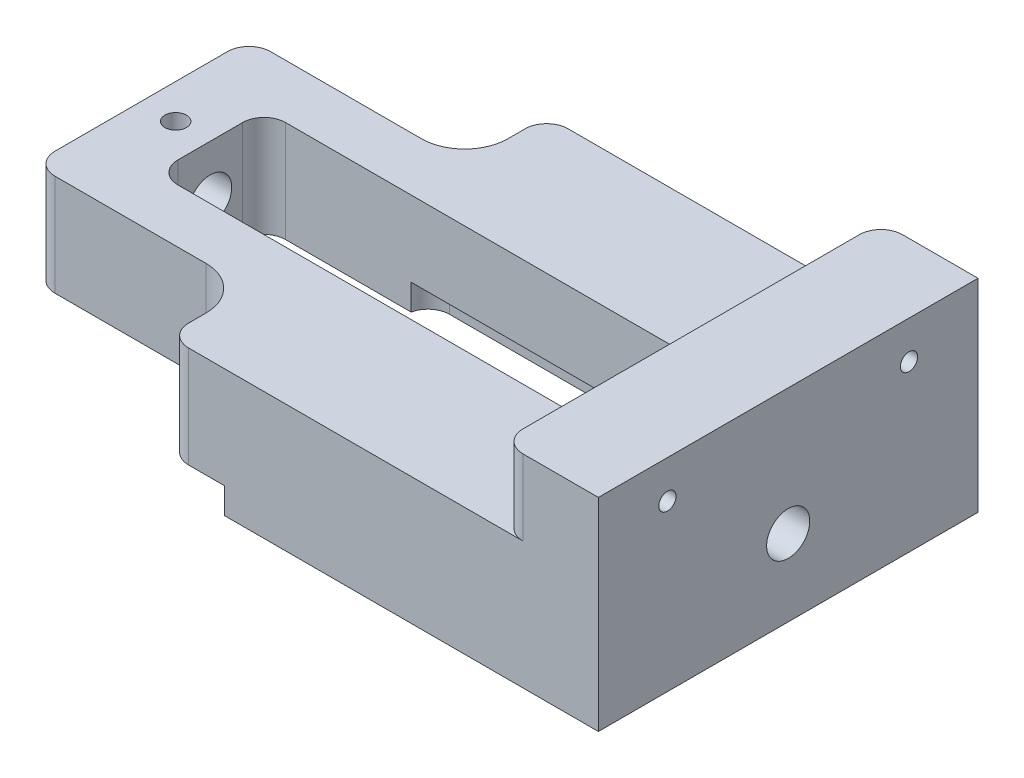
SolidWorks part; units mm, degrees
ref_plane "Front Plane" through (0, 0, 0) normal (0, 0, 1) x (1, 0, 0)
ref_plane "Top Plane" through (0, 0, 0) normal (0, 1, 0) x (1, 0, 0)
ref_plane "Right Plane" through (0, 0, 0) normal (1, 0, 0) x (0, 0, -1)
sketch "Sketch1" plane through (0, 0, 0) normal (0, 1, 0) x (1, 0, 0)
  line L0 (-256.2885, 0) -> (256.2885, 0) construction
  line L1 (-256.2885, 40) -> (-256.2885, -40)
  line L2 (-246.2885, -50) -> (-176.2885, -50)
  line L3 (-156.2885, -70) -> (-156.2885, -78)
  line L4 (-146.2885, -88) -> (43.7115, -88)
  line L5 (43.7115, -88) -> (43.7115, 88)
  line L6 (-146.2885, 88) -> (43.7115, 88)
  line L7 (-246.2885, 50) -> (-176.2885, 50)
  line L8 (-156.2885, 70) -> (-156.2885, 78)
  line L9 (-224.2885, 15) -> (-224.2885, -15)
  line L10 (-214.2885, -25) -> (-9.2885, -25)
  line L11 (0.7115, -15) -> (0.7115, 15)
  line L12 (-214.2885, 25) -> (-9.2885, 25)
  arc A0 (-156.2885, -70) -> (-176.2885, -50) centre (-176.2885, -70) ccw
  arc A1 (-246.2885, -50) -> (-256.2885, -40) centre (-246.2885, -40) cw
  arc A2 (-146.2885, -88) -> (-156.2885, -78) centre (-146.2885, -78) cw
  arc A3 (-146.2885, 88) -> (-156.2885, 78) centre (-146.2885, 78) ccw
  arc A4 (-156.2885, 70) -> (-176.2885, 50) centre (-176.2885, 70) cw
  arc A5 (-246.2885, 50) -> (-256.2885, 40) centre (-246.2885, 40) ccw
  arc A6 (0.7115, -15) -> (-9.2885, -25) centre (-9.2885, -15) cw
  arc A7 (-214.2885, -25) -> (-224.2885, -15) centre (-214.2885, -15) cw
  arc A8 (0.7115, 15) -> (-9.2885, 25) centre (-9.2885, 15) ccw
  arc A9 (-214.2885, 25) -> (-224.2885, 15) centre (-214.2885, 15) ccw
  point P0 (-56.2885, -88)
  point P4 (0, 0)
  point P12 (-156.2885, -50)
  point P15 (-256.2885, -50)
  point P18 (-156.2885, -88)
  point P29 (43.7115, 0)
  point P37 (-224.2885, -25)
  point P39 (0.7115, 0)
  point P44 (-224.2885, 0)
  dimension "D6" = 20
  dimension "D7" = 10
  dimension "D8" = 10
  dimension "D12" = 10
  dimension "D1" = 50
  dimension "D2" = 100
  dimension "D3" = 88
  dimension "D4" = 200
  dimension "D5" = 100
  dimension "D9" = 32
  dimension "D10" = 25
  dimension "D11" = 43
extrude "Boss-Extrude1" add sketch "Sketch1" along normal blind 47
sketch "Sketch2" plane through (0, 47, 0) normal (0, 1, 0) x (1, 0, 0)
  line L0 (43.7115, -88) -> (43.7115, 88) construction
  line L1 (43.7115, -88) -> (43.7115, 88)
  line L2 (43.7115, 88) -> (8.7115, 88)
  line L3 (43.7115, 88) -> (-146.2885, 88) construction
  line L4 (43.7115, -88) -> (8.7115, -88)
  line L5 (-146.2885, -88) -> (43.7115, -88) construction
  line L6 (-1.2885, -78) -> (-1.2885, 78)
  arc A0 (8.7115, -88) -> (-1.2885, -78) centre (8.7115, -78) cw
  arc A1 (-1.2885, 78) -> (8.7115, 88) centre (8.7115, 78) cw
  point P10 (-1.2885, -88)
  point P13 (-1.2885, 88)
  dimension "D2" = 10
  dimension "D1" = 45
extrude "Boss-Extrude2" add sketch "Sketch2" along normal blind 35
sketch "Sketch7" plane through (0, 0, 0) normal (0, -1, 0) x (1, 0, 0)
  line L0 (0, 0) -> (-137.9507, 0) construction
  line L1 (-129.6097, -88) -> (17.0327, -88)
  line L2 (43.7115, -88) -> (-146.2885, -88) construction
  line L3 (-129.6097, 88) -> (17.0327, 88)
  line L4 (43.7115, 88) -> (43.7115, -88) construction
  line L5 (43.7115, 88) -> (43.7115, -88)
  line L6 (43.7115, -88) -> (-1.2885, -88)
  line L7 (-1.2885, -88) -> (-1.2885, 88)
  line L8 (-1.2885, 88) -> (43.7115, 88)
  arc A0 (-1.2885, -61.9052) -> (-129.6097, -88) centre (-56.2885, -120) ccw
  arc A1 (-1.2885, 61.9052) -> (-129.6097, 88) centre (-56.2885, 120) cw
  dimension "D2" = 160
  dimension "D1" = 45
extrude "Boss-Extrude3" add sketch "Sketch7" along normal blind 12
sketch "Sketch3" plane through (-256.2885, 0, 0) normal (-1, 0, 0) x (0, 0, 1)
  line L0 (0, 0) -> (0, 82) construction
  line L1 (0, 82) -> (-63.2343, 82) construction
  line L2 (-78, 82) -> (78, 82) construction
  line L3 (-88, 82) -> (-88, 47) construction
  line L4 (-88, 82) -> (-88, 47)
  circle A0 centre (0, 23.5) radius 10
  circle A1 centre (-56, 64.5) radius 4
  circle A2 centre (56, 64.5) radius 4
  point P2 (0, 0)
  point P13 (0, 0)
  point P16 (-63.2343, 83)
  dimension "D1" = 20
  dimension "D3" = 8
  dimension "D2" = 56
  dimension "D4" = 17.5
extrude "Cut-Extrude1" cut sketch "Sketch3" against normal through all contours L0 A0 | A0 L0 | A2 | A1
sketch "Sketch6" plane through (0, 0, 0) normal (0, -1, 0) x (1, 0, 0)
  line L0 (-156.2885, -78) -> (-156.2885, -70) construction
  line L1 (-156.2885, -78) -> (-156.2885, -70)
  line L2 (-129.6097, -88) -> (-146.2885, -88) construction
  line L3 (0, 0) -> (-118.0061, 0) construction
  circle A0 centre (-56.2885, -65) radius 7.5
  circle A1 centre (-56.2885, 65) radius 7.5
  point P2 (-56.2885, -65)
  dimension "D3" = 15
  dimension "D1" = 100
  dimension "D2" = 23
extrude "Cut-Extrude3" cut sketch "Sketch6" along normal blind 12 contours A1 | A0
sketch "Sketch5" plane through (0, 0, 0) normal (0, -1, 0) x (1, 0, 0)
  line L0 (0, 23) -> (0, -23)
  line L1 (-10, -33) -> (-146.2885, -33)
  line L2 (0, 0) -> (-170.1654, 0) construction
  line L3 (-156.2885, -23) -> (-156.2885, 23)
  line L4 (-10, 33) -> (-146.2885, 33)
  arc A0 (0, -23) -> (-10, -33) centre (-10, -23) cw
  arc A1 (-146.2885, -33) -> (-156.2885, -23) centre (-146.2885, -23) cw
  arc A2 (0, 23) -> (-10, 33) centre (-10, 23) ccw
  arc A3 (-146.2885, 33) -> (-156.2885, 23) centre (-146.2885, 23) ccw
  point P9 (0, -33)
  point P18 (-156.2885, 0)
  dimension "D2" = 10
  dimension "D1" = 33
extrude "Cut-Extrude2" cut sketch "Sketch5" against normal blind 12
sketch "Sketch8" plane through (0, 47, 0) normal (0, 1, 0) x (1, 0, 0)
  line L0 (-256.2885, 0) -> (-224.2885, 0) construction
  line L1 (-256.2885, 40) -> (-256.2885, -40) construction
  line L2 (-224.2885, 15) -> (-224.2885, -15) construction
  circle A0 centre (-240.2885, 0) radius 5
  dimension "D1" = 10
extrude "Cut-Extrude4" cut sketch "Sketch8" against normal blind 14
